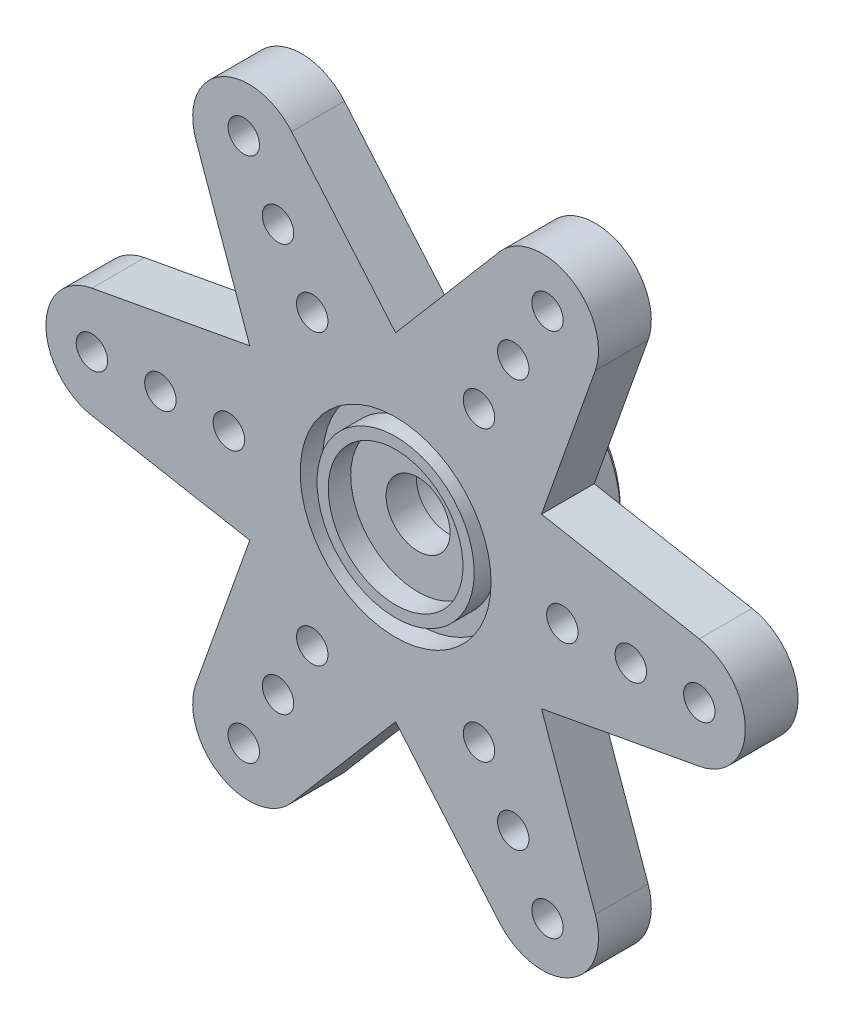
SolidWorks part; units mm, degrees
ref_plane "Plan de face" through (0, 0, 0) normal (0, 0, 1) x (1, 0, 0)
ref_plane "Plan de dessus" through (0, 0, 0) normal (0, 1, 0) x (1, 0, 0)
ref_plane "Plan de droite" through (0, 0, 0) normal (1, 0, 0) x (0, 0, -1)
ref_plane "Plan1" through (0, 0, 0) normal (0, 0, -1) x (-1, 0, 0)
sketch "Esquisse1" plane through (0, 0, 0) normal (0, 0, -1) x (-1, 0, 0)
  line L0 (0, 7.5) -> (-4.6331, 12.9424)
  line L1 (-8.8919, 10.4836) -> (-6.4952, 3.75)
  line L2 (-6.4952, 3.75) -> (-13.525, 2.4589)
  line L3 (-13.525, -2.4589) -> (-6.4952, -3.75)
  line L4 (-6.4952, -3.75) -> (-8.8919, -10.4836)
  line L5 (-4.6331, -12.9424) -> (0, -7.5)
  line L6 (0, -7.5) -> (4.6331, -12.9424)
  line L7 (8.8919, -10.4836) -> (6.4952, -3.75)
  line L8 (6.4952, -3.75) -> (13.525, -2.4589)
  line L9 (13.525, 2.4589) -> (6.4952, 3.75)
  line L10 (6.4952, 3.75) -> (8.8919, 10.4836)
  line L11 (4.6331, 12.9424) -> (0, 7.5)
  arc A0 (-4.6331, 12.9424) -> (-8.8919, 10.4836) centre (-6.5367, 11.3219) ccw
  arc A1 (-13.525, 2.4589) -> (-13.525, -2.4589) centre (-13.0734, 0) ccw
  arc A2 (-8.8919, -10.4836) -> (-4.6331, -12.9424) centre (-6.5367, -11.3219) ccw
  arc A3 (4.6331, -12.9424) -> (8.8919, -10.4836) centre (6.5367, -11.3219) ccw
  arc A4 (13.525, -2.4589) -> (13.525, 2.4589) centre (13.0734, 0) ccw
  arc A5 (8.8919, 10.4836) -> (4.6331, 12.9424) centre (6.5367, 11.3219) ccw
extrude "Boss.-Extru.1" add sketch "Esquisse1" against normal blind 2.35
hole_wizard "Diamètre du perçage Ø8.5 (8.5)1" positions "Esquisse3" profile "Esquisse2" hole size "Ø8.5" standard "Ansi Metric"
sketch "Esquisse3" plane through (0, 0, 2.35) normal (0, 0, 1) x (1, 0, 0)
  point P0 (0, 0)
sketch "Esquisse2" plane through (0, 0, 2.35) normal (1, 0, 0) x (0, -1, 0)
  line L0 (0, 0) -> (0, 1)
  line L1 (0, 1) -> (4.25, 1)
  line L2 (4.25, 1) -> (4.25, 0)
  line L5 (4.25, 0) -> (0, 0)
  line L10 (0, 1) -> (-4.25, 1) construction
  line L11 (0, -6.35) -> (0, 107.95) construction
  dimension "Diamètre du perçage" = 8.5
  dimension "Profondeur du perçage" = 1
  dimension "Angle de pointe" = 180
sketch "Esquisse4" plane through (0, 0, 0) normal (0, 1, 0) x (1, 0, 0)
  line L0 (4.4, 3.5) -> (0, 3.5)
  line L1 (0, 3.5) -> (0, 0)
  line L2 (0, 0) -> (4.4, 0)
  line L3 (4.4, 0) -> (4.4, 3.5)
  line L4 (0, 3.5) -> (0, 0) construction
revolve "Révolution1" add sketch "Esquisse4" angle 360 about L4
sketch "Esquisse5" plane through (0, 0, 0) normal (0, 1, 0) x (1, 0, 0)
  line L0 (3.5, -1.35) -> (0, -1.35)
  line L1 (0, -1.35) -> (0, -2.35)
  line L2 (0, -2.35) -> (3.5, -2.35)
  line L3 (3.5, -2.35) -> (3.5, -1.35)
  line L4 (0, -1.35) -> (0, -2.35) construction
revolve "Révolution2" add sketch "Esquisse5" angle 360 about L4
ref_plane "Plan2" through (0, 0, 0) normal (0, -1, 0) x (1, 0, 0)
sketch "Esquisse6" plane through (0, 0, 0) normal (0, -1, 0) x (1, 0, 0)
  line L0 (3, 2.35) -> (0, 2.35)
  line L1 (0, 2.35) -> (0, -3.5)
  line L2 (0, -3.5) -> (2.65, -3.5)
  line L3 (2.65, -3.5) -> (2.65, 0)
  line L4 (2.65, 0) -> (1.425, 0)
  line L5 (1.425, 0) -> (1.425, 1.35)
  line L6 (1.425, 1.35) -> (3, 1.35)
  line L7 (3, 1.35) -> (3, 2.35)
  line L8 (0, 2.35) -> (0, -3.5) construction
revolve "Enlèvement de matière-Révolution1" cut sketch "Esquisse6" angle 360 about L8
hole_wizard "Diamètre du perçage Ø1.4 (1.4)1" positions "Esquisse8" profile "Esquisse7" hole size "Ø1.4" standard "Ansi Metric"
sketch "Esquisse8" plane through (0, 0, 2.35) normal (0, 0, 1) x (1, 0, 0)
  point P0 (6.7625, 11.713)
  point P1 (3.7125, 6.4302)
  point P2 (-5.2375, 9.0716)
  point P3 (-13.525, 0)
  point P4 (-7.425, 0)
  point P5 (-5.2375, -9.0716)
  point P6 (6.7625, -11.713)
  point P7 (3.7125, -6.4302)
  point P8 (10.475, 0)
  point P9 (7.425, 0)
  point P10 (13.525, 0)
  point P11 (5.2375, -9.0716)
  point P12 (-3.7125, -6.4302)
  point P13 (-6.7625, -11.713)
  point P14 (-10.475, 0)
  point P15 (-3.7125, 6.4302)
  point P16 (-6.7625, 11.713)
  point P17 (5.2375, 9.0716)
sketch "Esquisse7" plane through (6.7625, 11.713, 2.35) normal (1, 0, 0) x (0, -1, 0)
  line L0 (0, 0) -> (0, 5.85)
  line L1 (0, 5.85) -> (0.7, 5.85)
  line L2 (0.7, 5.85) -> (0.7, 0)
  line L5 (0.7, 0) -> (0, 0)
  line L11 (0, -6.35) -> (0, 107.95) construction
  dimension "Diamètre du perçage jusqu'au prochain" = 1.4
  dimension "Profondeur du perçage jusqu'au prochain" = 5.85
chamfer "Chanfrein1" distance 0.25 angle 45 1 edges at (4.4, 0, -3.5)
